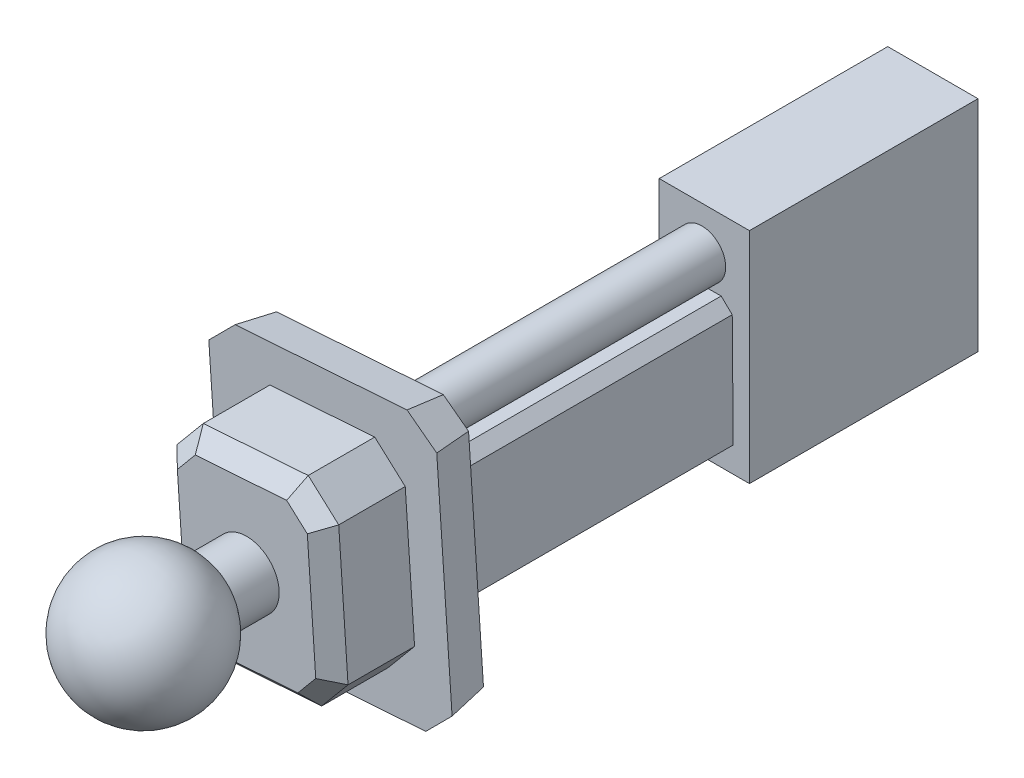
SolidWorks part; units mm, degrees
ref_plane "Front Plane" through (0, 0, 0) normal (0, 0, 1) x (1, 0, 0)
ref_plane "Top Plane" through (0, 0, 0) normal (0, 1, 0) x (1, 0, 0)
ref_plane "Right Plane" through (0, 0, 0) normal (1, 0, 0) x (0, 0, -1)
sketch "Sketch1" plane through (0, 0, 0) normal (0, 0, 1) x (1, 0, 0)
  line L1 (117.396, 310.8975) -> (141.4884, 310.8975)
  line L2 (117.396, 310.8975) -> (117.396, 252.3985)
  line L3 (117.396, 252.3985) -> (141.4884, 252.3985)
  line L4 (141.4884, 310.8975) -> (141.4884, 252.3985)
extrude "Boss-Extrude1" add sketch "Sketch1" along normal blind 61.0164
sketch "Sketch2" plane through (0, 0, 61.0164) normal (0, 0, 1) x (1, 0, 0)
  line L0 (128.7973, 305.6348) -> (128.7973, 292.9412) construction
  line L1 (118.6269, 289.0142) -> (121.5367, 291.9067)
  line L2 (121.5367, 291.9067) -> (133.9352, 292.0058)
  line L3 (133.9352, 292.0058) -> (136.892, 289.162)
  line L4 (136.892, 289.162) -> (137.1536, 259.1659)
  line L5 (137.1536, 259.1659) -> (134.2408, 256.2728)
  line L6 (134.2408, 256.2728) -> (121.8316, 256.1712)
  line L7 (121.8316, 256.1712) -> (118.8885, 259.0183)
  line L8 (118.8885, 259.0183) -> (118.6269, 289.0142)
  circle A0 centre (128.7973, 299.288) radius 6.3468
  point P2 (128.6866, 305.6339)
  point P3 (128.7973, 292.9412)
extrude "Boss-Extrude2" add sketch "Sketch2" along normal blind 83.7336
sketch "Sketch3" plane through (0, 0, 144.75) normal (0, 0, 1) x (1, 0, 0)
  line L0 (92.9734, 306.7279) -> (98.9444, 312.7136)
  line L1 (98.9444, 312.7136) -> (143.4882, 315.8513)
  line L2 (143.4882, 315.8513) -> (150.2306, 310.7609)
  line L3 (150.2306, 310.7609) -> (154.2113, 253.6121)
  line L4 (154.2113, 253.6121) -> (148.2402, 247.6261)
  line L5 (148.2402, 247.6261) -> (103.6963, 244.4887)
  line L6 (103.6963, 244.4887) -> (96.9538, 249.5789)
  line L7 (96.9538, 249.5789) -> (92.9734, 306.7279)
extrude "Boss-Extrude3" add sketch "Sketch3" along normal blind 10.2359 draft 10 draft outward yes
sketch "Sketch4" plane through (0, 0, 154.986) normal (0, 0, 1) x (1, 0, 0)
  line L0 (100.3689, 296.7218) -> (107.4102, 305.1429)
  line L1 (107.4102, 305.1429) -> (135.4178, 307.1157)
  line L2 (135.4178, 307.1157) -> (143.5578, 299.7639)
  line L3 (143.5578, 299.7639) -> (146.0475, 264.0195)
  line L4 (146.0475, 264.0195) -> (139.0061, 255.5984)
  line L5 (139.0061, 255.5984) -> (110.9985, 253.6256)
  line L6 (110.9985, 253.6256) -> (102.8583, 260.9774)
  line L7 (102.8583, 260.9774) -> (100.3689, 296.7218)
extrude "Boss-Extrude4" add sketch "Sketch4" along normal blind 22.0119
chamfer "Chamfer1" distance 4.256 angle 45 8 edges at (139.4878, 303.4398, 176.9979) (144.8026, 281.8917, 176.9979) (142.5268, 259.809, 176.9979) (125.0023, 254.612, 176.9979) (106.9284, 257.3015, 176.9979) (101.6136, 278.8496, 176.9979) (103.8896, 300.9323, 176.9979) (121.414, 306.1293, 176.9979)
sketch "Sketch5" plane through (0, 0, 176.9979) normal (0, 0, 1) x (1, 0, 0)
  line L0 (121.7121, 301.8837) -> (124.7042, 258.8576) construction
  line L1 (133.9096, 302.7429) -> (109.5145, 301.0245) construction
  line L2 (112.5066, 257.9984) -> (136.9019, 259.7168) construction
  point P6 (123.2082, 280.3707)
ref_plane "Plane1" through (123.2082, 0, 0) normal (1, 0, 0) x (0, 0, -1)
sketch "Sketch6" plane through (123.2082, 0, 0) normal (1, 0, 0) x (0, 0, -1)
  line L0 (-176.9979, 280.3707) -> (-176.9979, 289.0895)
  line L1 (-176.9979, 301.8837) -> (-176.9979, 258.8576) construction
  line L2 (-176.9979, 289.0895) -> (-188.3494, 289.0895)
  line L3 (-176.9979, 280.3707) -> (-222.9538, 280.3707)
  arc A0 (-188.3494, 289.0895) -> (-222.9538, 280.3707) centre (-204.5532, 280.3707) ccw
  dimension "D4" = 18.4006
  dimension "D1" = 8.7188
  dimension "D2" = 45.956
  dimension "D3" = 11.3515
revolve "Revolve1" add sketch "Sketch6" angle 360 about L3
move or copy body "Body-Move/Copy1" [suppressed] bodies to move or copy 105
